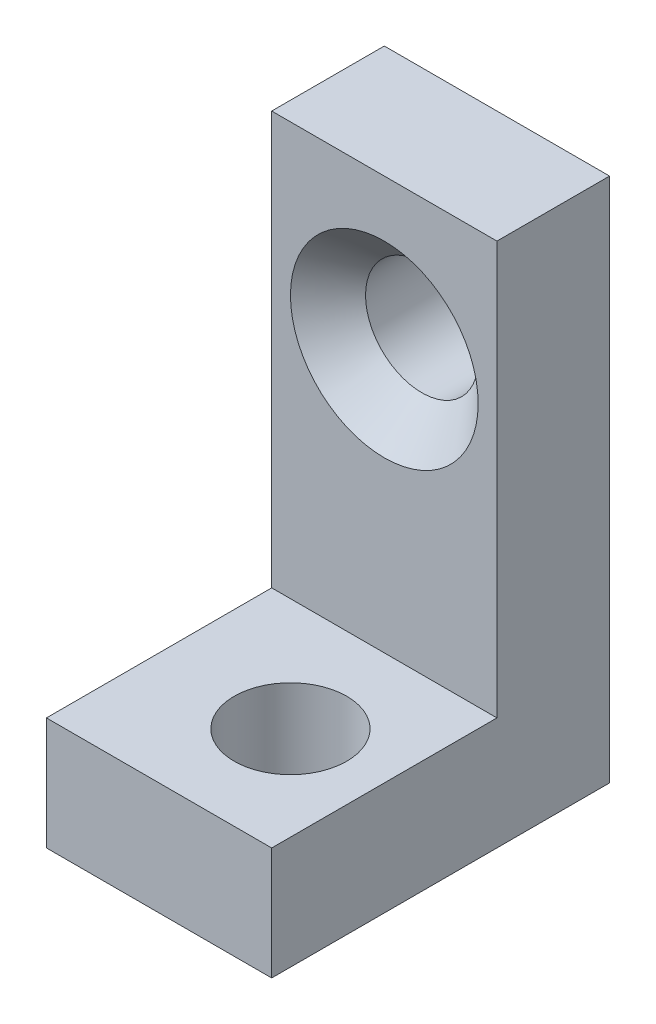
SolidWorks part; units mm, degrees
ref_plane "Plan de face" through (0, 0, 0) normal (0, 0, 1) x (1, 0, 0)
ref_plane "Plan de dessus" through (0, 0, 0) normal (0, 1, 0) x (1, 0, 0)
ref_plane "Plan de droite" through (0, 0, 0) normal (1, 0, 0) x (0, 0, -1)
sketch "Esquisse1" plane through (0, 0, 0) normal (0, 0, 1) x (1, 0, 0)
  line L1 (-4.0274, -7.0137) -> (1.9726, -7.0137)
  line L2 (-4.0274, -7.0137) -> (-4.0274, 6.9863)
  line L3 (-4.0274, 6.9863) -> (1.9726, 6.9863)
  line L4 (1.9726, -7.0137) -> (1.9726, 6.9863)
  line L5 (-4.0274, -7.0137) -> (1.9726, 6.9863) construction
  line L6 (-4.0274, 6.9863) -> (1.9726, -7.0137) construction
  circle A0 centre (-1.0274, 2.9863) radius 1.5
  point P0 (-1.0274, -0.0137)
  dimension "D3" = 4
  dimension "D4" = 3
  dimension "D1" = 6
  dimension "D2" = 14
  dimension "D5" = 3
extrude "Boss.-Extru.1" add sketch "Esquisse1" along normal blind 3
sketch "Esquisse2" plane through (0, 0, 3) normal (0, 0, 1) x (1, 0, 0)
  line L1 (-4.0274, -7.0137) -> (1.9726, -7.0137)
  line L2 (-4.0274, -7.0137) -> (-4.0274, -4.0137)
  line L3 (-4.0274, -4.0137) -> (1.9726, -4.0137)
  line L4 (1.9726, -7.0137) -> (1.9726, -4.0137)
  dimension "D1" = 3
  dimension "D2" = 6
extrude "Boss.-Extru.2" add sketch "Esquisse2" along normal blind 6
sketch "Esquisse3" plane through (0, -7.0137, 0) normal (0, -1, 0) x (-1, 0, 0)
  line L0 (-1.9726, -9) -> (-1.9726, 0) construction
  line L1 (4.0274, 0) -> (-1.9726, 0) construction
  circle A0 centre (0.5274, -6) radius 1.5
  dimension "D1" = 6
  dimension "D3" = 3
  dimension "D2" = 2.5
extrude "Enlèv. mat.-Extru.1" cut sketch "Esquisse3" against normal blind 10 contours A0
chamfer "Chanfrein3" distance 1 angle 45 1 edges at (0.4726, 2.9863, 3)
